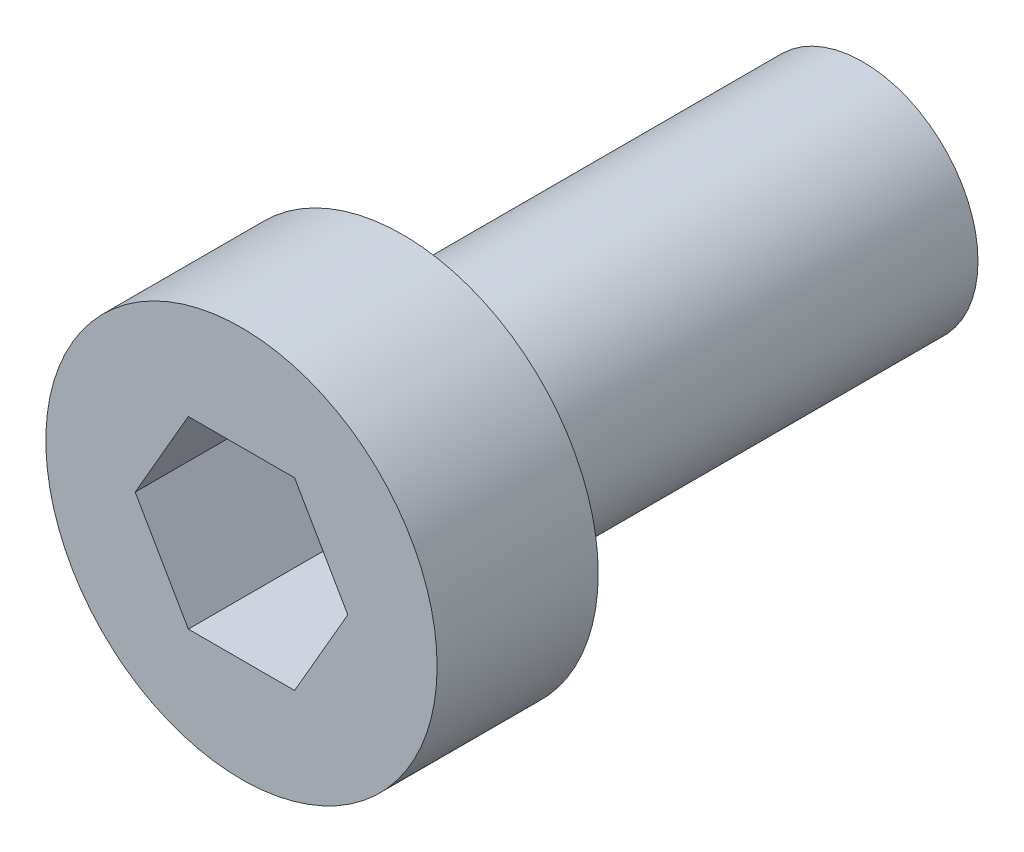
SolidWorks part; units mm, degrees
ref_plane "Plan de face" through (0, 0, 0) normal (0, 0, 1) x (1, 0, 0)
ref_plane "Plan de dessus" through (0, 0, 0) normal (0, 1, 0) x (1, 0, 0)
ref_plane "Plan de droite" through (0, 0, 0) normal (1, 0, 0) x (0, 0, -1)
sketch "Esquisse1" plane through (0, 0, 0) normal (0, 0, 1) x (1, 0, 0)
  circle A0 centre (0, 0) radius 2.5
  dimension "D1" = 5
extrude "Boss.-Extru.1" add sketch "Esquisse1" along normal blind 10
sketch "Esquisse2" plane through (0, 0, 10) normal (0, 0, 1) x (1, 0, 0)
  circle A0 centre (0, 0) radius 4.25
  dimension "D1" = 8.5
extrude "Boss.-Extru.2" add sketch "Esquisse2" along normal blind 3.5
sketch "Esquisse3" plane through (0, 0, 13.5) normal (0, 0, 1) x (1, 0, 0)
  line L1 (2.3094, 0) -> (1.1547, 2)
  line L2 (1.1547, 2) -> (-1.1547, 2)
  line L3 (-1.1547, 2) -> (-2.3094, 0)
  line L4 (-2.3094, 0) -> (-1.1547, -2)
  line L5 (-1.1547, -2) -> (1.1547, -2)
  line L6 (1.1547, -2) -> (2.3094, 0)
  circle A0 centre (0, 0) radius 2 construction
  dimension "D1" = 4
extrude "Enlèv. mat.-Extru.1" cut sketch "Esquisse3" against normal blind 3.5
